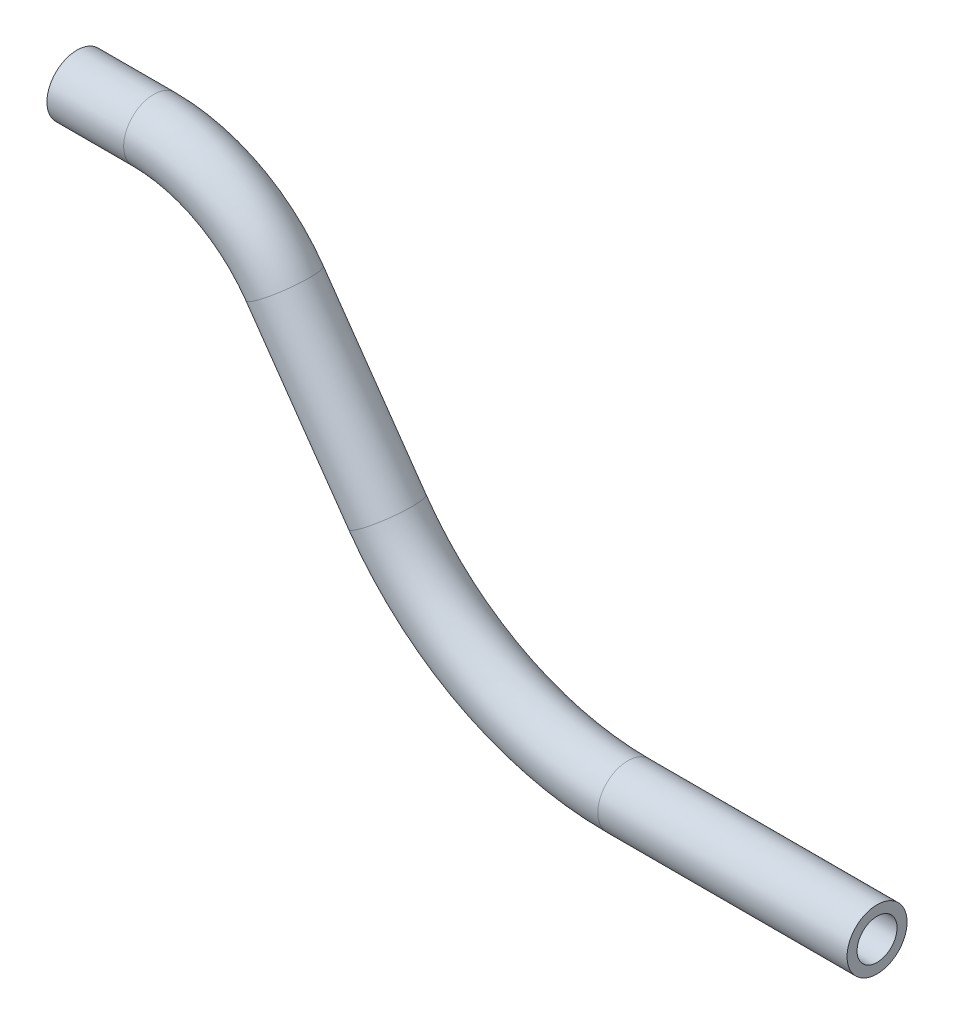
SolidWorks part; units mm, degrees
ref_plane "Front Plane" through (0, 0, 0) normal (0, 0, 1) x (1, 0, 0)
ref_plane "Top Plane" through (0, 0, 0) normal (0, 1, 0) x (1, 0, 0)
ref_plane "Right Plane" through (0, 0, 0) normal (1, 0, 0) x (0, 0, -1)
sketch "Sketch2" plane through (0, 0, 0) normal (0, 0, 1) x (1, 0, 0)
  line L0 (0, 0) -> (57.532, 0)
  line L1 (155.8302, -51.1708) -> (232.8642, -161.1868)
  line L2 (413.0777, -255) -> (600, -255)
  arc A0 (232.8642, -161.1868) -> (413.0777, -255) centre (413.0777, -35) ccw
  arc A1 (57.532, 0) -> (155.8302, -51.1708) centre (57.532, -120) cw
  point P7 (228.7747, -57.7656)
  point P10 (120, 0)
  dimension "D5" = 220
  dimension "D6" = 120
  dimension "D1" = 120
  dimension "D2" = 600
  dimension "D3" = 255
  dimension "D4" = 125
sketch "Sketch3" plane through (0, 0, 0) normal (1, 0, 0) x (0, 0, -1)
  circle A0 centre (0, 0) radius 15
  circle A1 centre (0, 0) radius 22.5
  dimension "D1" = 30
  dimension "D2" = 45
sweep "Sweep1" add profiles "Sketch3" path "Sketch2"
